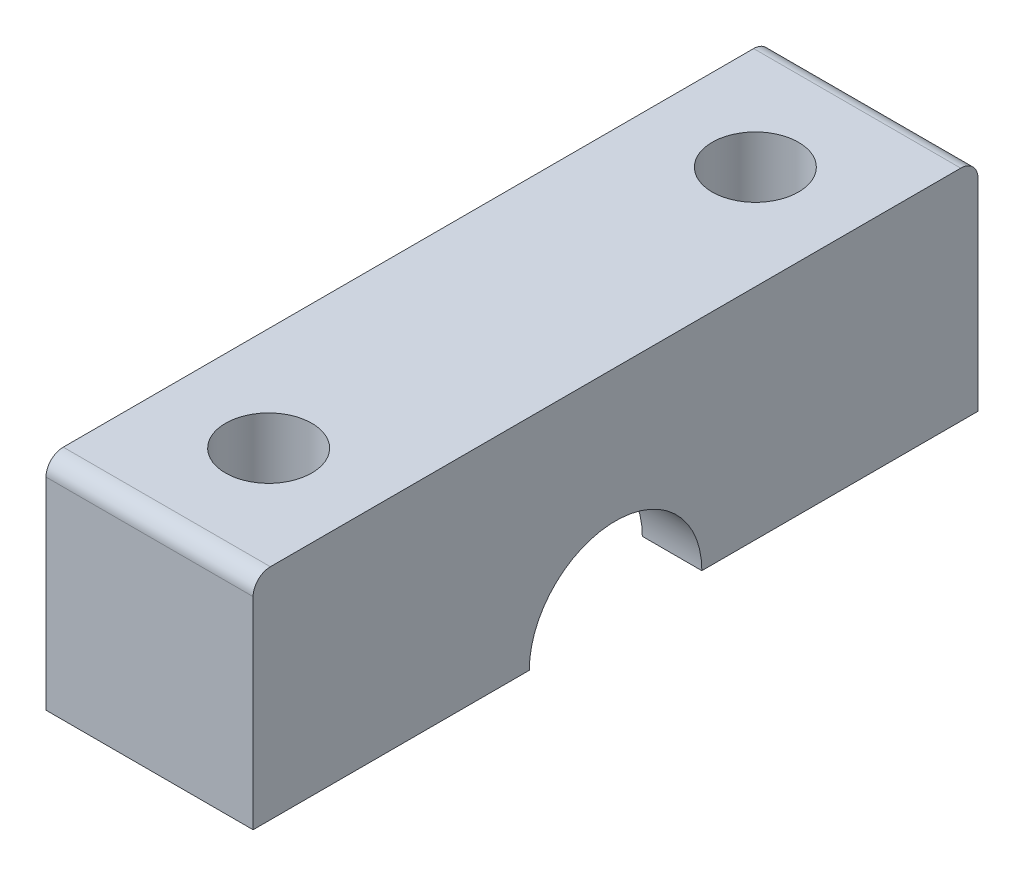
SolidWorks part; units mm, degrees
ref_plane "Front Plane" through (0, 0, 0) normal (0, 0, 1) x (1, 0, 0)
ref_plane "Top Plane" through (0, 0, 0) normal (0, 1, 0) x (1, 0, 0)
ref_plane "Right Plane" through (0, 0, 0) normal (1, 0, 0) x (0, 0, -1)
sketch "Sketch1" plane through (100, 0, 0) normal (1, 0, 0) x (0, 0, -1)
  line L0 (0, 23) -> (0, 35.7)
  line L1 (0, 35.7) -> (42, 35.7)
  line L2 (42, 35.7) -> (42, 23)
  line L3 (26, 23) -> (42, 23)
  line L4 (16, 23) -> (0, 23)
  arc A3 (26, 23) -> (16, 23) centre (21, 23) ccw
  arc A4 (16, 23) -> (26, 23) centre (21, 23) ccw construction
  dimension "D1" = 12.7
extrude "Boss-Extrude1" add sketch "Sketch1" against normal up to surface (12 mm away) contours L2 L3 A3 L4 L0 L1
ref_plane "Plane1" through (94, 0, 0) normal (1, 0, 0) x (0, 0, -1)
sketch "Sketch2" plane through (94, 0, 0) normal (1, 0, 0) x (0, 0, -1)
  circle A0 centre (21, 23) radius 8.5
  arc A1 (26, 23) -> (16, 23) centre (21, 23) ccw construction
  dimension "D1" = 17
extrude "Cut-Extrude1" cut sketch "Sketch2" against normal mid plane 5.1
sketch "Sketch3" plane through (0, 35.7, 0) normal (0, 1, 0) x (1, 0, 0)
  circle A0 centre (94, 35.1) radius 2.5
  circle A1 centre (94, 6.9) radius 2.5
  dimension "D1" = 5
extrude "Cut-Extrude2" cut sketch "Sketch3" against normal up to next
fillet "Fillet1" radius 1 2 edges at (94, 35.7, -42) (94, 35.7, 0)
